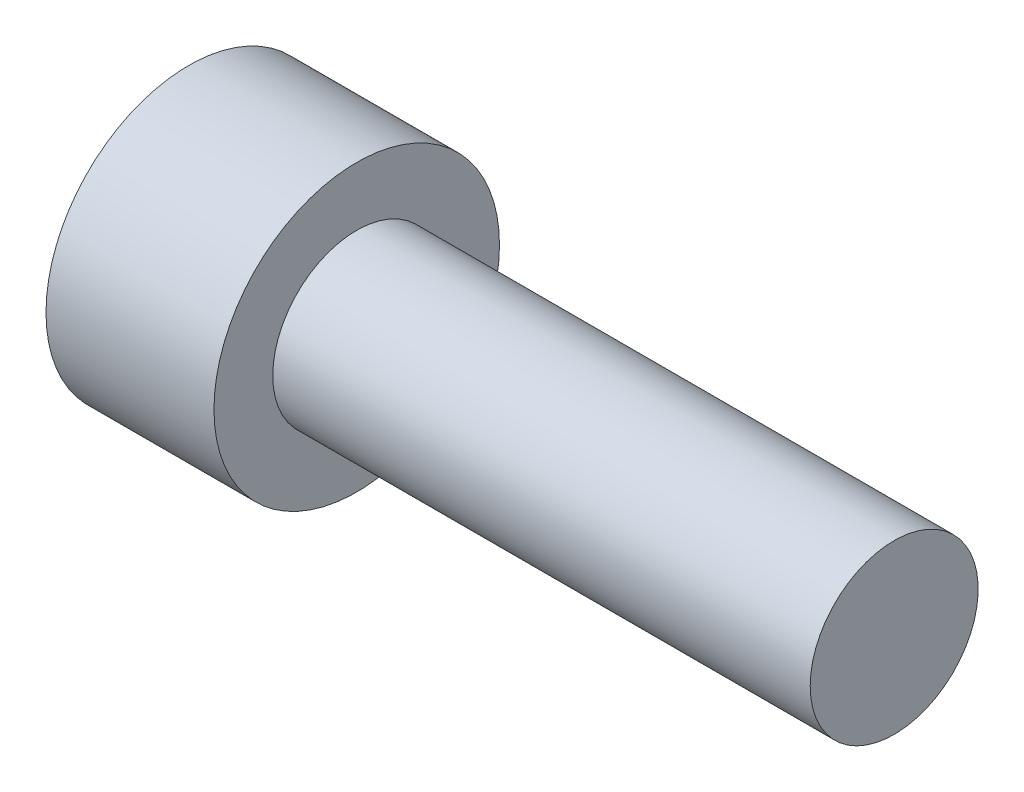
SolidWorks part; units mm, degrees
ref_plane "Front Plane" through (0, 0, 0) normal (0, 0, 1) x (1, 0, 0)
ref_plane "Top Plane" through (0, 0, 0) normal (0, 1, 0) x (1, 0, 0)
ref_plane "Right Plane" through (0, 0, 0) normal (1, 0, 0) x (0, 0, -1)
sketch "Sketch1" plane through (0, 0, 0) normal (0, 0, 1) x (1, 0, 0)
  line L0 (0, 0) -> (21, 0) construction
  line L3 (0, 0) -> (0, 4.25)
  line L4 (0, 4.25) -> (5, 4.25)
  line L5 (5, 2.5) -> (5, 4.25)
  line L6 (5, 2.5) -> (21, 2.5)
  line L8 (0, 0) -> (21, 0)
  line L9 (21, 2.5) -> (21, 0)
  dimension "CS_A" = 8.5
  dimension "CS_E" = 5
  dimension "CS_L" = 16
  dimension "CS_M" = 5
revolve "Revolve1" add sketch "Sketch1" angle 360 about L0
cosmetic thread "Cosmetic Thread1" parameters "CS_L"=16, "CS_D_s"=4.134
sketch "Sketch2" plane through (0, 0, 0) normal (0, 0, 1) x (1, 0, 0)
  line L0 (0, 0) -> (21, 0) construction
  line L1 (0, 4.25) -> (0, -4.25) construction
  line L2 (21, -2.5) -> (21, 2.5) construction
  line L3 (0, 2) -> (2.5, 2)
  line L4 (2.5, 2) -> (3.6547, 0)
  line L5 (0, 2) -> (0, 0)
  line L6 (0, 0) -> (3.6547, 0)
  dimension "D1" = 60
  dimension "CS_T_s" = 2.5
  dimension "CS_B" = 4
revolve "Cut-Revolve1" cut sketch "Sketch2" angle 360 about L0
sketch "Sketch3" plane through (0, 0, 0) normal (-1, 0, 0) x (0, 0, 1)
  line L0 (0, 0) -> (0, 4.25) construction
  line L1 (0, -2.3094) -> (2, -1.1547)
  line L2 (2, -1.1547) -> (2, 1.1547)
  line L3 (2, 1.1547) -> (0, 2.3094)
  line L4 (0, 2.3094) -> (-2, 1.1547)
  line L5 (-2, 1.1547) -> (-2, -1.1547)
  line L6 (-2, -1.1547) -> (0, -2.3094)
  circle A0 centre (0, 0) radius 2 construction
  circle A1 centre (0, 0) radius 4.25 construction
  circle A2 centre (0, 0) radius 2 construction
extrude "Cut-Extrude1" cut sketch "Sketch3" against normal blind 2.5
